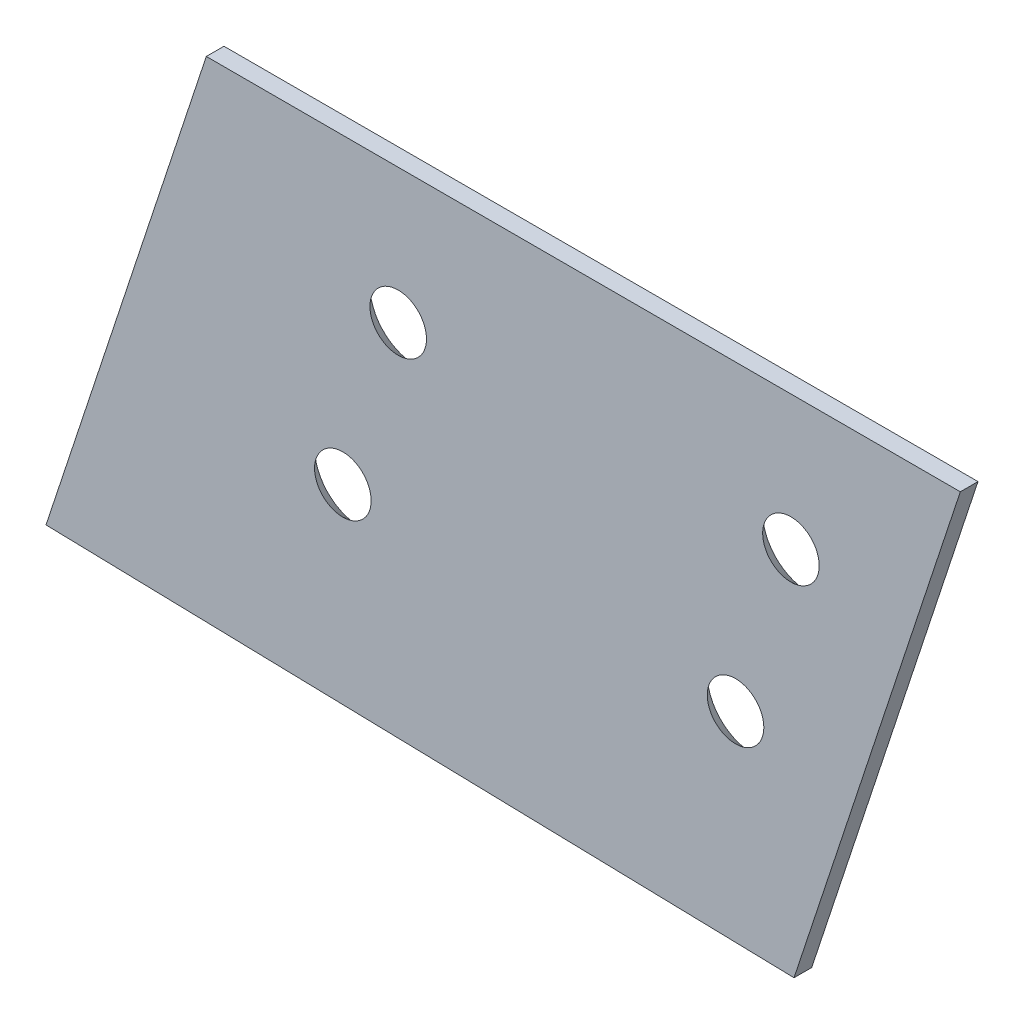
SolidWorks part; units mm, degrees
ref_plane "Front Plane" through (0, 0, 0) normal (0, 0, 1) x (1, 0, 0)
ref_plane "Top Plane" through (0, 0, 0) normal (0, 1, 0) x (1, 0, 0)
ref_plane "Right Plane" through (0, 0, 0) normal (1, 0, 0) x (0, 0, -1)
sketch "Sketch2" plane through (0, 0, 0) normal (0, 0, 1) x (1, 0, 0)
  line L0 (-54.6192, -24.5892) -> (30.7248, -24.5892)
  line L1 (-54.6192, -24.5892) -> (-71.4913, -75.7257)
  line L2 (30.7248, -24.5892) -> (13.8527, -75.7257)
  line L3 (-71.4913, -75.7257) -> (13.8527, -75.7257)
  dimension "D1" = 85.344
  dimension "D2" = 53.848
  dimension "D3" = 108.26
extrude "Boss-Extrude1" add sketch "Sketch2" along normal blind 2
sketch "Sketch3" plane through (0, 0, 2) normal (0, 0, 1) x (1, 0, 0)
  line L0 (-72.7647, -79.585) -> (11.9014, -81.6395)
  line L2 (-71.4913, -75.7257) -> (-72.7647, -79.585)
  line L3 (-72.7647, -79.585) -> (18.6346, -79.585) construction
  line L4 (-54.6192, -24.5892) -> (-71.4913, -75.7257) construction
  line L5 (13.8527, -75.7257) -> (11.9014, -81.6395)
  line L6 (13.8527, -75.7257) -> (30.7248, -24.5892) construction
  line L7 (-71.4913, -75.7257) -> (13.8527, -75.7257)
  dimension "D1" = 1.39
  dimension "D2" = 180
  dimension "D3" = 180
  dimension "D4" = 4.064
extrude "Boss-Extrude2" add sketch "Sketch3" against normal blind 2
sketch "Sketch4" plane through (0, 0, 2) normal (0, 0, 1) x (1, 0, 0)
  line L0 (-32.9007, -39.8292) -> (-39.1673, -58.8221) construction
  line L1 (-39.1673, -58.8221) -> (5.2827, -58.8221) construction
  line L2 (5.2827, -58.8221) -> (11.5493, -39.8292) construction
  line L3 (11.5493, -39.8292) -> (-32.9007, -39.8292) construction
  line L4 (-54.6192, -24.5892) -> (-72.7647, -79.585) construction
  line L5 (30.7248, -24.5892) -> (-54.6192, -24.5892) construction
  circle A0 centre (-32.9007, -39.8292) radius 2.5
  circle A1 centre (11.5493, -39.8292) radius 2.5
  circle A2 centre (5.2827, -58.8221) radius 2.5
  circle A3 centre (-39.1673, -58.8221) radius 2.5
  dimension "D1" = 5
  dimension "D2" = 44.45
  dimension "D3" = 20
  dimension "D4" = 25.4
  dimension "D5" = 15.24
extrude "Cut-Extrude2" cut sketch "Sketch4" against normal up to surface (2 mm away) up to face at (-21.1894, -52.6007, 0)
hole_wizard "CSK for M5 Flat Head Machine Screw1" positions "3DSketch1" profile "Sketch5" countersink size "M5" standard "ANSI Metric" end condition through all
sketch3d "3DSketch1"
  line L0 (11.5493, -39.8292, 0) -> (11.5493, -39.8292, 2) construction
  line L1 (-32.9007, -39.8292, 0) -> (-32.9007, -39.8292, 2) construction
  line L2 (-39.1673, -58.8221, 0) -> (-39.1673, -58.8221, 2) construction
  line L3 (5.2827, -58.8221, 0) -> (5.2827, -58.8221, 2) construction
  point P0 (11.5493, -39.8292, 0)
  point P4 (-32.9007, -39.8292, 0)
  point P8 (-39.1673, -58.8221, 0)
  point P12 (5.2827, -58.8221, 0)
sketch "Sketch5" plane through (11.5493, -39.8292, 0) normal (1, 0, 0) x (0, 1, 0)
  line L0 (0, 0) -> (0, 2)
  line L1 (0, 2) -> (2.75, 2)
  line L2 (2.75, 2) -> (2.75, 2.45)
  line L3 (2.75, 2.45) -> (5.2, 0)
  line L5 (5.2, 0) -> (0, 0)
  line L6 (-2.75, 2.45) -> (-5.2, 0) construction
  line L11 (0, -6.35) -> (0, 107.95) construction
  dimension "Thru Hole Dia." = 5.5
  dimension "Thru Hole Depth" = 2
  dimension "Near C'Sink Dia." = 10.4
  dimension "Near C'Sink Angle" = 90
